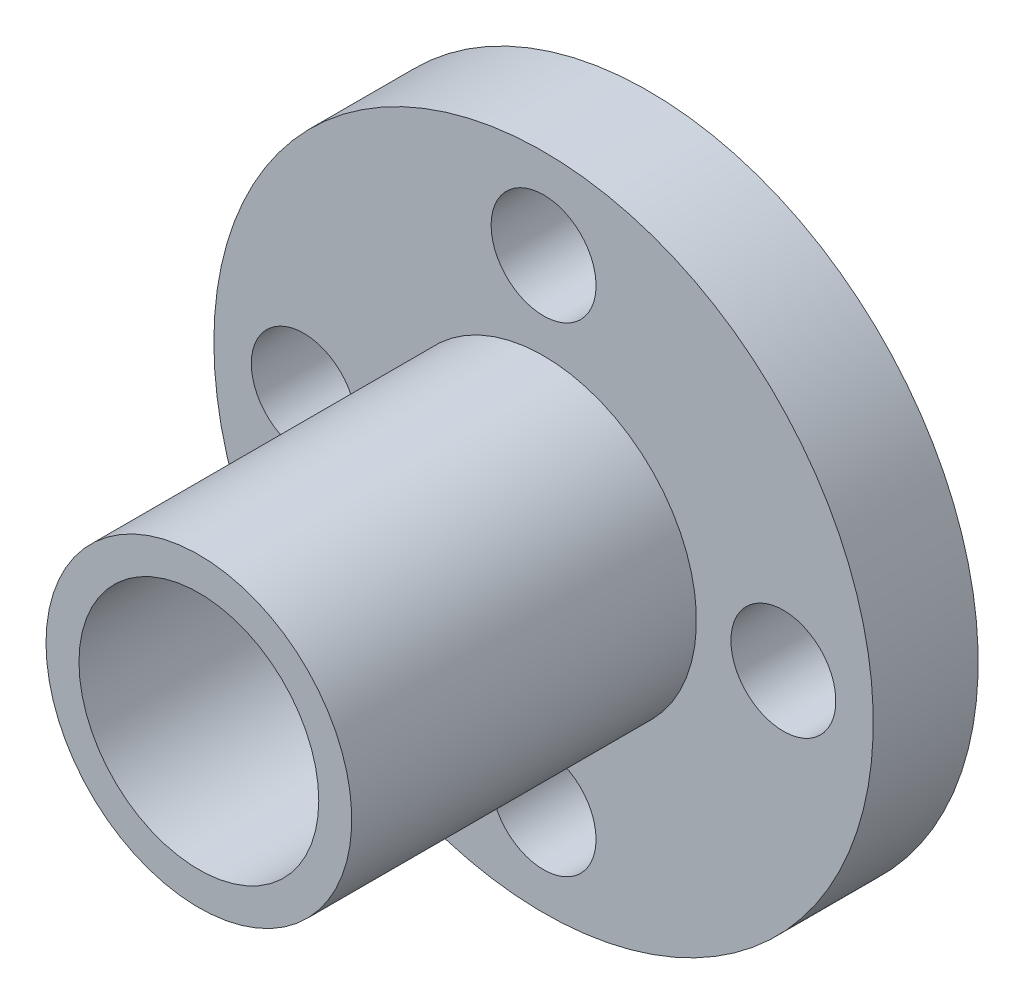
SolidWorks part; units mm, degrees
material "黄铜"
ref_plane "前视基准面" through (0, 0, 0) normal (0, 0, 1) x (1, 0, 0)
ref_plane "上视基准面" through (0, 0, 0) normal (0, 1, 0) x (1, 0, 0)
ref_plane "右视基准面" through (0, 0, 0) normal (1, 0, 0) x (0, 0, -1)
sketch "草图1" plane through (0, 0, 0) normal (0, 1, 0) x (1, 0, 0)
  line L0 (0, 35.9174) -> (0, 0) construction
  line L1 (0, 0) -> (31.9947, 0) construction
  line L2 (4, 15) -> (4, 0)
  line L3 (4, 0) -> (5.1, 0)
  line L4 (5.1, 0) -> (5.1, 11.5)
  line L5 (5.1, 11.5) -> (11, 11.5)
  line L6 (11, 11.5) -> (11, 15)
  line L7 (11, 15) -> (4, 15)
  dimension "D1" = 3.5
  dimension "D2" = 8
  dimension "D3" = 10.2
  dimension "D4" = 15
  dimension "D5" = 22
revolve "旋转1" add sketch "草图1" angle 360 about L0
sketch "草图2" plane through (0, 0, -15) normal (0, 0, -1) x (-1, 0, 0)
  circle A0 centre (0, 0) radius 8 construction
  circle A1 centre (0, 8) radius 1.75
  circle A2 centre (8, 0) radius 1.75
  circle A3 centre (0, -8) radius 1.75
  circle A4 centre (-8, 0) radius 1.75
  dimension "D1" = 16
  dimension "D2" = 3.5
  dimension "D3" = 4
extrude "切除-拉伸1" cut sketch "草图2" against normal through all
